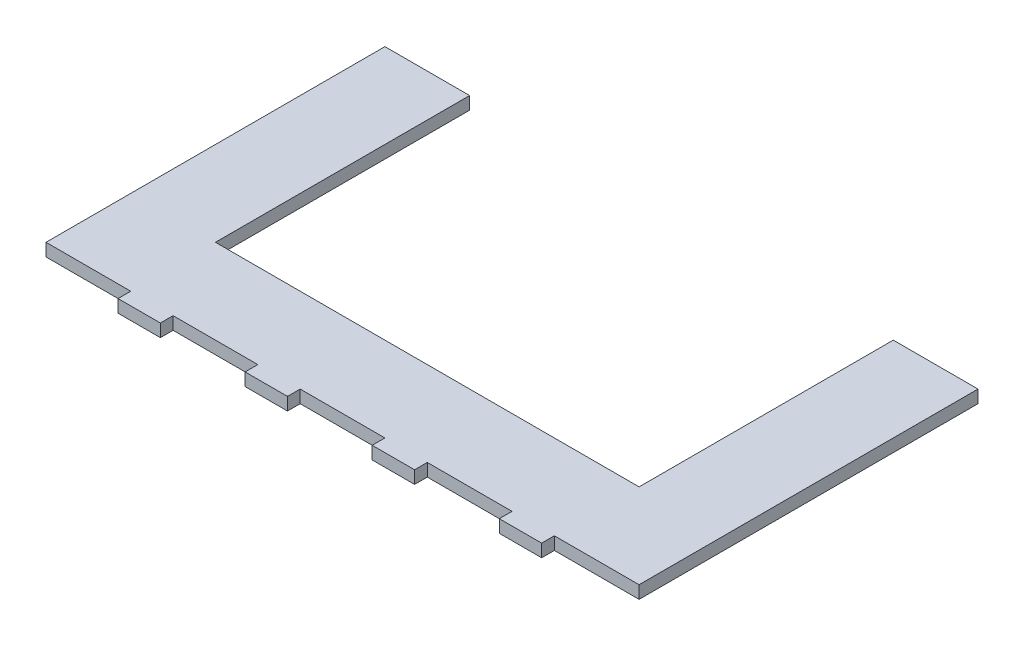
SolidWorks part; units mm, degrees
ref_plane "Front Plane" through (0, 0, 0) normal (0, 0, 1) x (1, 0, 0)
ref_plane "Top Plane" through (0, 0, 0) normal (0, 1, 0) x (1, 0, 0)
ref_plane "Right Plane" through (0, 0, 0) normal (1, 0, 0) x (0, 0, -1)
sketch "Sketch1" plane through (0, 0, 0) normal (0, 1, 0) x (1, 0, 0)
  line L1 (-70, 40) -> (70, 40)
  line L2 (-70, 40) -> (-70, -40)
  line L3 (-70, -40) -> (70, -40)
  line L4 (70, 40) -> (70, -40)
  line L5 (-70, 40) -> (70, -40) construction
  line L6 (-70, -40) -> (70, 40) construction
  point P0 (0, 0)
  dimension "D1" = 80
  dimension "D2" = 140
extrude "Boss-Extrude1" add sketch "Sketch1" along normal blind 3
sketch "Sketch2" plane through (0, 3, 0) normal (0, 1, 0) x (1, 0, 0)
  line L8 (70, 40) -> (-70, 40) construction
  line L9 (-50, 40) -> (50, 40)
  line L10 (-50, 40) -> (-50, -20)
  line L11 (-50, -20) -> (50, -20)
  line L12 (50, 40) -> (50, -20)
  line L13 (-70, 40) -> (-70, -40) construction
  line L14 (70, -40) -> (70, 40) construction
  line L15 (-70, -40) -> (70, -40) construction
  dimension "D1" = 20
  dimension "D2" = 20
  dimension "D3" = 20
extrude "Cut-Extrude1" cut sketch "Sketch2" against normal blind 13
sketch "Sketch4" plane through (0, 0, 40) normal (0, 0, 1) x (1, 0, 0)
  line L0 (-70, 3) -> (70, 3) construction
  line L1 (-50, 3) -> (-40, 3)
  line L2 (-50, 3) -> (-50, 0)
  line L3 (-50, 0) -> (-40, 0)
  line L4 (-40, 3) -> (-40, 0)
  line L5 (-70, 0) -> (70, 0) construction
  line L6 (-70, 3) -> (-70, 0) construction
  line L7 (-20, 3) -> (-20, 0)
  line L8 (-20, 3) -> (-10, 3)
  line L9 (-10, 3) -> (-10, 0)
  line L10 (-20, 0) -> (-10, 0)
  line L11 (10, 3) -> (10, 0)
  line L12 (10, 3) -> (20, 3)
  line L13 (20, 3) -> (20, 0)
  line L14 (10, 0) -> (20, 0)
  line L15 (40, 3) -> (40, 0)
  line L16 (40, 3) -> (50, 3)
  line L17 (50, 3) -> (50, 0)
  line L18 (40, 0) -> (50, 0)
  point P10 (-40, 1.5)
  dimension "D1" = 20
  dimension "D2" = 10
  dimension "D3" = 4
extrude "Boss-Extrude2" add sketch "Sketch4" along normal blind 3
